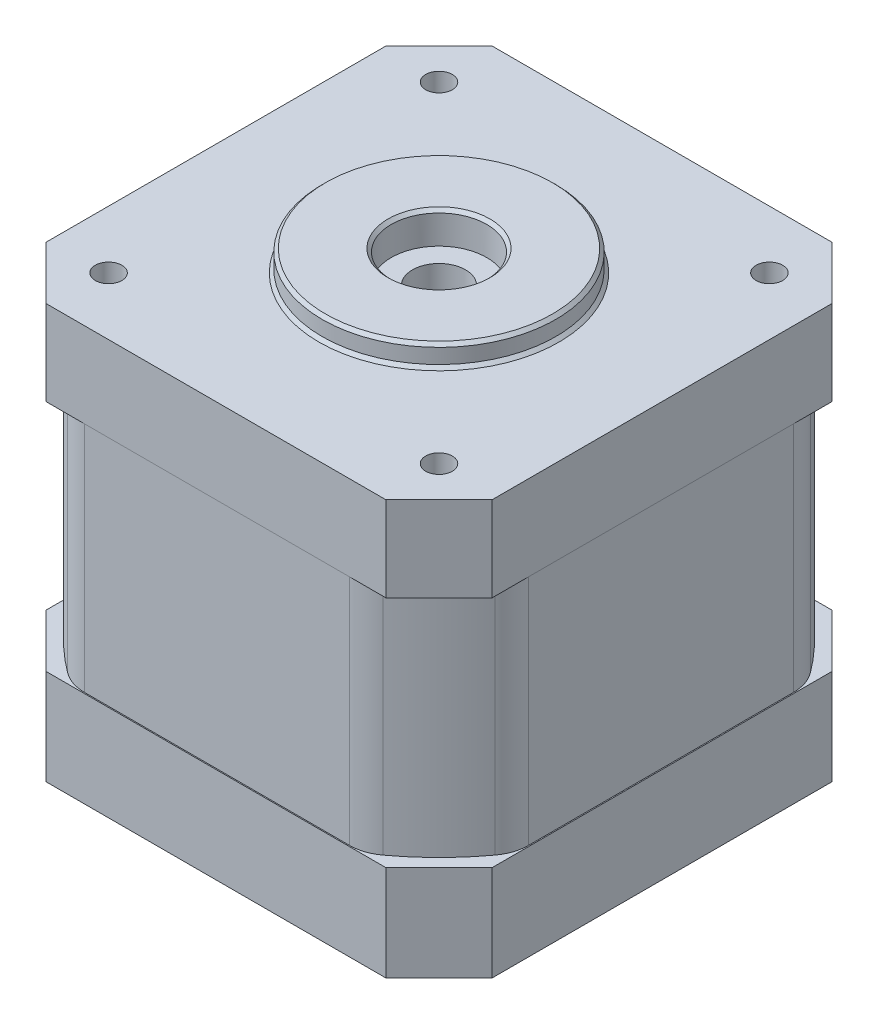
SolidWorks part; units mm, degrees
ref_plane "Face" through (0, 0, 0) normal (0, 0, 1) x (1, 0, 0)
ref_plane "Dessus" through (0, 0, 0) normal (0, 1, 0) x (1, 0, 0)
ref_plane "Droite" through (0, 0, 0) normal (1, 0, 0) x (0, 0, -1)
sketch "Esquisse1" plane through (0, 0, 0) normal (0, 1, 0) x (1, 0, 0)
  line L0 (-21, 0) -> (21, 0) construction
  line L1 (-21, 21) -> (21, 21)
  line L2 (-21, 21) -> (-21, -21)
  line L3 (-21, -21) -> (21, -21)
  line L4 (21, 21) -> (21, -21)
  dimension "D1" = 42
extrude "Boss.-Extru.1" add sketch "Esquisse1" against normal blind 8
chamfer "Chanfrein1" distance 5 angle 45 4 edges at (-21, -4, -21) (-21, -4, 21) (21, -4, -21) (21, -4, 21)
sketch "Esquisse2" plane through (0, 0, 0) normal (0, -1, 0) x (-1, 0, 0)
  circle A0 centre (0, 0) radius 11
  dimension "D1" = 22
extrude "Boss.-Extru.2" add sketch "Esquisse2" against normal blind 2
sketch "Esquisse5" plane through (0, 2, 0) normal (0, 1, 0) x (1, 0, 0)
  circle A0 centre (0, 0) radius 4.5
  dimension "D1" = 9
extrude "Enlèv. mat.-Extru.1" cut sketch "Esquisse5" against normal blind 3
chamfer "Chanfrein2" distance 0.3 angle 45 3 edges at (0, 2, -11) (0, 2, 4.5) (0, 0, 11)
sketch "Esquisse6" plane through (0, -8, 0) normal (0, -1, 0) x (1, 0, 0)
  line L79 (20.9, 15.9586) -> (15.9586, 20.9)
  line L80 (15.9586, -20.9) -> (20.9, -15.9586)
  line L81 (-20.9, -15.9586) -> (-15.9586, -20.9)
  line L82 (-15.9586, 20.9) -> (-20.9, 15.9586)
  line L83 (20.9, -15.9586) -> (20.9, 15.9586)
  line L84 (-15.9586, -20.9) -> (15.9586, -20.9)
  line L85 (-20.9, 15.9586) -> (-20.9, -15.9586)
  line L86 (15.9586, 20.9) -> (-15.9586, 20.9)
  line L91 (20.9, -13.7182) -> (20.9, 13.7182)
  line L92 (-13.7182, -20.9) -> (13.7182, -20.9)
  line L93 (-20.9, 13.7182) -> (-20.9, -13.7182)
  line L94 (13.7182, 20.9) -> (-13.7182, 20.9)
  arc A0 (20.9, 13.7182) -> (13.7182, 20.9) centre (0, 0) ccw
  arc A1 (13.7182, -20.9) -> (20.9, -13.7182) centre (0, 0) ccw
  arc A2 (-20.9, -13.7182) -> (-13.7182, -20.9) centre (0, 0) ccw
  arc A3 (-13.7182, 20.9) -> (-20.9, 13.7182) centre (0, 0) ccw
  dimension "D1" = 0.1
  dimension "D2" = 50
extrude "Boss.-Extru.3" add sketch "Esquisse6" along normal blind 22
fillet "Congé1" radius 4 8 edges at (-20.9, -19, 13.7182) (-20.9, -19, -13.7182) (-13.7182, -19, -20.9) (13.7182, -19, -20.9) (20.9, -19, -13.7182) (20.9, -19, 13.7182) (13.7182, -19, 20.9) (-13.7182, -19, 20.9)
sketch "Esquisse7" plane through (0, -30, 0) normal (0, -1, 0) x (1, 0, 0)
  line L8 (-16, -21) -> (16, -21)
  line L9 (-21, -16) -> (-16, -21)
  line L10 (-21, 16) -> (-21, -16)
  line L11 (-16, 21) -> (-21, 16)
  line L12 (16, 21) -> (-16, 21)
  line L13 (21, 16) -> (16, 21)
  line L14 (21, -16) -> (21, 16)
  line L15 (16, -21) -> (21, -16)
  line L16 (-16, -21) -> (16, -21)
  line L17 (-21, -16) -> (-16, -21)
  line L18 (-21, 16) -> (-21, -16)
  line L19 (-16, 21) -> (-21, 16)
  line L20 (16, 21) -> (-16, 21)
  line L21 (21, 16) -> (16, 21)
  line L22 (21, -16) -> (21, 16)
  line L23 (16, -21) -> (21, -16)
  dimension "D1" = 0
extrude "Boss.-Extru.4" add sketch "Esquisse7" along normal blind 9
sketch "Esquisse8" plane through (0, -39, 0) normal (0, -1, 0) x (1, 0, 0)
  circle A0 centre (0, 0) radius 4.5
  dimension "D1" = 9
extrude "Enlèv. mat.-Extru.2" cut sketch "Esquisse8" against normal blind 3
hole_wizard "Trou taraudé M31" positions "Esquisse4" profile "Esquisse3" tap size "M3" standard "Iso" end condition through all
sketch "Esquisse4" plane through (-18.1602, 0, -3.6427) normal (0, -1, 0) x (-1, 0, 0)
  line L0 (-18.1602, -3.6427) -> (0.3398, 14.8573) construction
  line L1 (-2.1602, 17.3573) -> (2.8398, 12.3573) construction
  line L2 (-18.1602, -3.6427) -> (-36.6602, 14.8573) construction
  line L3 (-39.1602, 12.3573) -> (-34.1602, 17.3573) construction
  line L4 (-18.1602, -3.6427) -> (-36.6602, -22.1427) construction
  line L5 (-34.1602, -24.6427) -> (-39.1602, -19.6427) construction
  line L6 (-18.1602, -3.6427) -> (0.3398, -22.1427) construction
  line L7 (2.8398, -19.6427) -> (-2.1602, -24.6427) construction
  circle A0 centre (-18.1602, -3.6427) radius 22 construction
  point P0 (-33.7166, -19.199)
  point P2 (-33.7166, 11.9137)
  point P4 (-2.6039, 11.9137)
  point P6 (-2.6039, -19.199)
  dimension "D1" = 44
sketch "Esquisse3" plane through (15.5563, 0, 15.5563) normal (1, 0, 0) x (0, 0, 1)
  line L0 (0, 0) -> (0, 39)
  line L1 (0, 39) -> (1.25, 39)
  line L2 (1.25, 39) -> (1.25, 0)
  line L5 (1.25, 0) -> (0, 0)
  line L11 (0, -6.35) -> (0, 107.95) construction
  dimension "Diamètre du trou pour taraudage jusqu'au prochain" = 2.5
  dimension "Profondeur du trou pour taraudage jusqu'au prochain" = 39
cosmetic thread "Filetage de perçage5" parameters "D2"=3
cosmetic thread "Filetage de perçage6" parameters "D2"=3
cosmetic thread "Filetage de perçage7" parameters "D2"=3
cosmetic thread "Filetage de perçage8" parameters "D2"=3
sketch "Esquisse9" plane through (0, -1, 0) normal (0, 1, 0) x (1, 0, 0)
  circle A0 centre (0, 0) radius 2.5
  dimension "D1" = 5
extrude "Enlèv. mat.-Extru.3" cut sketch "Esquisse9" against normal through all
